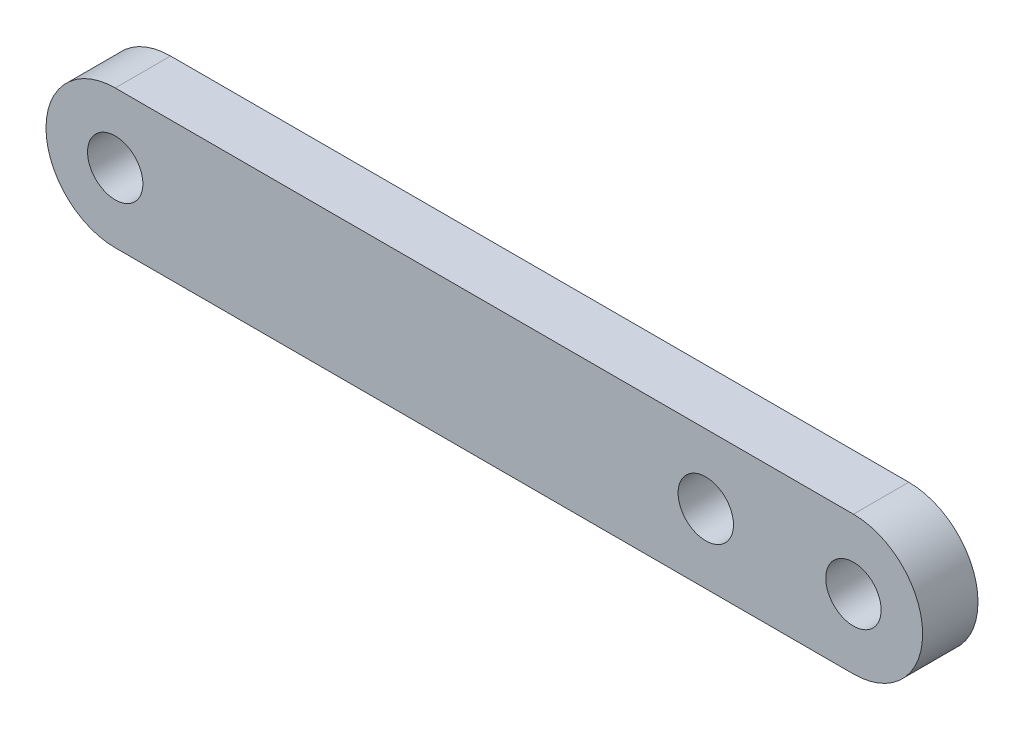
SolidWorks part; units mm, degrees
ref_plane "Front Plane" through (0, 0, 0) normal (0, 0, 1) x (1, 0, 0)
ref_plane "Top Plane" through (0, 0, 0) normal (0, 1, 0) x (1, 0, 0)
ref_plane "Right Plane" through (0, 0, 0) normal (1, 0, 0) x (0, 0, -1)
sketch "Sketch1" plane through (0, 0, 0) normal (0, 0, 1) x (1, 0, 0)
  line L0 (0, 3.75) -> (40, 3.75)
  line L1 (40, -3.75) -> (0, -3.75)
  circle A0 centre (0, 0) radius 1.5
  circle A1 centre (40, 0) radius 1.5
  circle A2 centre (32, 0) radius 1.5
  circle A3 centre (0, 0) radius 3.75
  circle A4 centre (40, 0) radius 3.75
  dimension "D2" = 3
  dimension "D3" = 3
  dimension "D4" = 3
  dimension "D6" = 7.5
  dimension "D1" = 40
  dimension "D5" = 8
extrude "Boss-Extrude1" add sketch "Sketch1" along normal blind 3 contours A4 L0 A3 L1 A2 | A3 A0 | A4 A1
